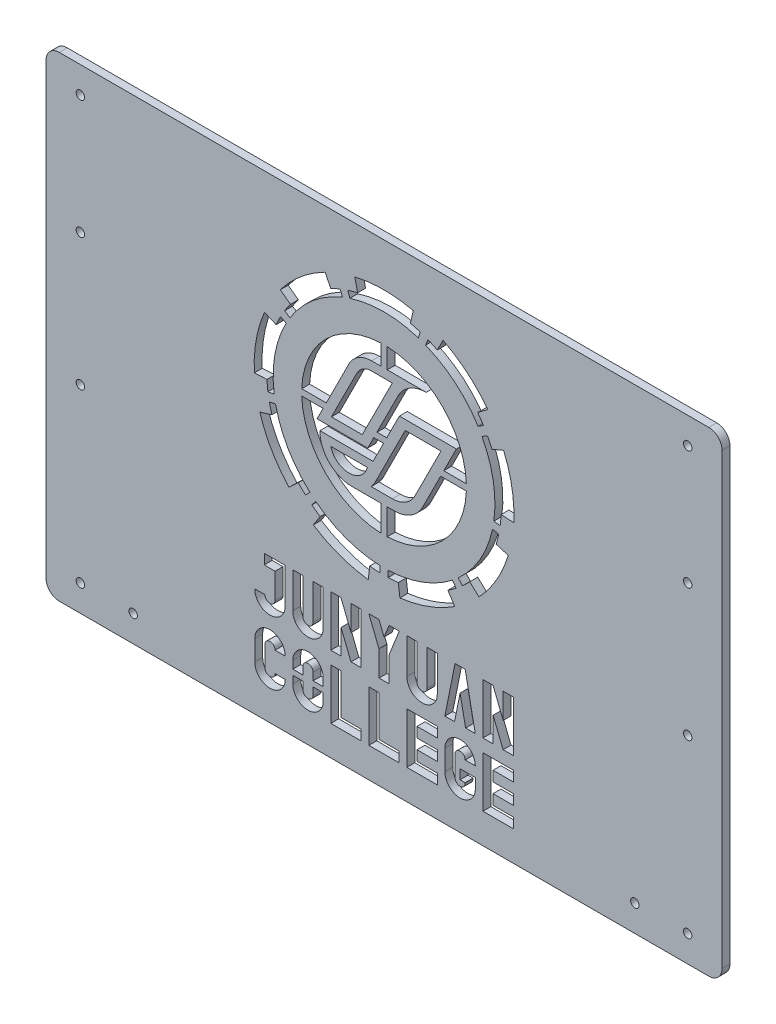
SolidWorks part; units mm, degrees
material "Thornel Mat VMA"
ref_plane "Front Plane" through (0, 0, 0) normal (0, 0, 1) x (1, 0, 0)
ref_plane "Top Plane" through (0, 0, 0) normal (0, 1, 0) x (1, 0, 0)
ref_plane "Right Plane" through (0, 0, 0) normal (1, 0, 0) x (0, 0, -1)
sketch "Model" plane through (0, 0, 0) normal (0, 0, 1) x (1, 0, 0)
  line L0 (140.7037, 160.9684) -> (141.7835, 165.6454)
  line L1 (120.728, 160.9684) -> (119.6483, 165.6454)
  line L2 (110.5587, 157.2671) -> (108.3795, 161.5439)
  line L3 (95.2564, 144.427) -> (91.423, 147.3157)
  line L4 (89.8454, 135.0549) -> (85.427, 136.9304)
  line L5 (86.3767, 115.3827) -> (81.5833, 115.1315)
  line L6 (88.2559, 104.7251) -> (83.6657, 103.3217)
  line L7 (98.2438, 87.4257) -> (94.7333, 84.1521)
  line L8 (106.5339, 80.4694) -> (103.9196, 76.4438)
  line L9 (125.3049, 73.6374) -> (124.7199, 68.8731)
  line L10 (136.1269, 73.6374) -> (136.7118, 68.8731)
  line L11 (154.8978, 80.4694) -> (157.5121, 76.4438)
  line L12 (163.188, 87.4257) -> (166.6985, 84.1521)
  line L13 (173.1758, 104.7251) -> (177.7661, 103.3217)
  line L14 (175.055, 115.3827) -> (179.8484, 115.1315)
  line L15 (171.5863, 135.0549) -> (176.0047, 136.9304)
  line L16 (166.1753, 144.427) -> (170.0087, 147.3157)
  line L17 (150.873, 157.2671) -> (153.0522, 161.5439)
  line L18 (136.5243, 128.4339) -> (158.1243, 128.4339)
  line L19 (138.745, 124.8339) -> (152.2882, 124.8339)
  line L20 (136.5243, 128.4339) -> (131.7401, 118.9064)
  line L21 (130.535, 116.5064) -> (126.5615, 108.5934)
  line L22 (138.745, 124.8339) -> (127.4637, 102.3677)
  line L23 (126.5615, 108.5934) -> (106.429, 108.5934)
  line L24 (124.4082, 105.5236) -> (110.5023, 105.5236)
  line L25 (158.1243, 128.4339) -> (153.3401, 118.9064)
  line L26 (152.135, 116.5064) -> (145.3412, 102.9771)
  line L27 (152.2882, 124.8339) -> (142.4563, 105.2541)
  line L28 (118.4268, 96.3621) -> (129.5159, 96.3621)
  line L29 (131.9159, 96.3621) -> (134.6174, 96.3621)
  line L30 (125.8338, 99.9621) -> (133.8771, 99.9621)
  line L31 (124.5428, 111.9383) -> (105.3428, 111.9383)
  line L32 (122.4702, 115.2983) -> (110.7898, 115.2983)
  line L33 (135.9593, 134.6735) -> (128.0418, 118.9064)
  line L34 (126.8367, 116.5064) -> (124.5428, 111.9383)
  line L35 (133.8339, 137.9285) -> (122.4702, 115.2983)
  line L36 (117.4236, 135.9965) -> (108.8418, 118.9064)
  line L37 (107.6367, 116.5064) -> (105.3428, 111.9383)
  line L38 (120.4263, 134.4887) -> (110.7898, 115.2983)
  line L39 (126.0027, 141.2885) -> (129.5159, 141.2885)
  line L40 (131.9159, 141.2885) -> (146.6831, 141.2885)
  line L41 (87.2861, 108.4751) -> (89.6337, 108.9741)
  line L42 (116.9955, 159.9333) -> (117.7371, 157.6508)
  line L43 (169.9187, 138.551) -> (167.7997, 137.4242)
  line L44 (126.0027, 137.9285) -> (133.8339, 137.9285)
  line L45 (160.4253, 84.7108) -> (158.8193, 86.4943)
  line L46 (114.0833, 158.8734) -> (114.9824, 156.6481)
  line L47 (86.748, 111.5271) -> (89.1246, 111.8611)
  line L48 (168.3692, 141.2348) -> (166.3339, 139.963)
  line L49 (158.0512, 82.7187) -> (156.5736, 84.61)
  line L50 (129.5159, 141.2885) -> (129.5159, 148.8833)
  line L51 (131.9159, 141.2885) -> (131.9159, 148.8833)
  line L52 (129.5159, 96.3621) -> (129.5159, 86.5295)
  line L53 (131.9159, 96.3621) -> (131.9159, 86.5295)
  line L54 (99.5389, 118.9064) -> (108.8418, 118.9064)
  line L55 (107.6367, 116.5064) -> (99.5389, 116.5064)
  line L56 (153.3401, 118.9064) -> (161.8928, 118.9064)
  line L57 (152.135, 116.5064) -> (161.8928, 116.5064)
  line L58 (128.0418, 118.9064) -> (131.7401, 118.9064)
  line L59 (126.8367, 116.5064) -> (130.535, 116.5064)
  line L60 (85.3559, 57.848) -> (93.2759, 57.848)
  line L61 (93.2759, 57.848) -> (93.2759, 44.408)
  line L62 (85.3559, 57.848) -> (85.3559, 54.008)
  line L63 (85.3559, 54.008) -> (89.4359, 54.008)
  line L64 (89.4359, 54.008) -> (89.4359, 44.408)
  line L65 (85.5959, 44.408) -> (81.7559, 44.408)
  line L66 (107.6759, 57.848) -> (107.6759, 44.408)
  line L67 (103.8359, 57.848) -> (103.8359, 44.408)
  line L68 (103.8359, 57.848) -> (107.6759, 57.848)
  line L69 (96.1559, 57.848) -> (96.1559, 44.408)
  line L70 (99.9959, 57.848) -> (99.9959, 44.408)
  line L71 (99.9959, 57.848) -> (96.1559, 57.848)
  line L72 (122.0759, 57.848) -> (122.0759, 38.648)
  line L73 (118.2359, 57.848) -> (118.2359, 48.248)
  line L74 (110.5559, 57.848) -> (110.5559, 38.648)
  line L75 (114.4323, 48.0636) -> (114.4673, 38.648)
  line L76 (114.3959, 57.848) -> (118.2359, 48.248)
  line L77 (114.4323, 48.0636) -> (118.1985, 38.648)
  line L78 (122.0759, 38.648) -> (118.1985, 38.648)
  line L79 (110.5559, 57.848) -> (114.3959, 57.848)
  line L80 (118.2359, 57.848) -> (122.0759, 57.848)
  line L81 (110.5559, 38.648) -> (114.4673, 38.648)
  line L82 (128.7959, 48.248) -> (128.8309, 38.648)
  line L83 (128.7959, 57.848) -> (130.7159, 53.048)
  line L84 (124.9559, 57.848) -> (128.7959, 57.848)
  line L85 (132.6359, 57.848) -> (136.4759, 57.848)
  line L86 (132.6359, 57.848) -> (130.7159, 53.048)
  line L87 (124.9559, 57.848) -> (128.7959, 48.248)
  line L88 (136.4759, 57.848) -> (132.6359, 48.248)
  line L89 (132.6359, 48.248) -> (132.6008, 38.648)
  line L90 (128.8309, 38.648) -> (132.6008, 38.648)
  line L91 (150.8759, 57.848) -> (150.8759, 44.408)
  line L92 (147.0359, 57.848) -> (147.0359, 44.408)
  line L93 (147.0359, 57.848) -> (150.8759, 57.848)
  line L94 (139.3559, 57.848) -> (139.3559, 44.408)
  line L95 (143.1959, 57.848) -> (143.1959, 44.408)
  line L96 (143.1959, 57.848) -> (139.3559, 57.848)
  line L97 (165.2759, 38.648) -> (161.6046, 38.648)
  line L98 (153.7559, 38.648) -> (157.4272, 38.648)
  line L99 (153.7559, 38.648) -> (157.5959, 57.848)
  line L100 (157.4272, 38.648) -> (159.5159, 49.0915)
  line L101 (157.5959, 57.848) -> (161.4359, 57.848)
  line L102 (161.4359, 57.848) -> (165.2759, 38.648)
  line L103 (161.6046, 38.648) -> (159.5159, 49.0915)
  line L104 (179.6759, 57.848) -> (179.6759, 38.648)
  line L105 (175.8359, 57.848) -> (175.8359, 48.248)
  line L106 (168.1559, 57.848) -> (168.1559, 38.648)
  line L107 (172.0323, 48.0636) -> (172.0673, 38.648)
  line L108 (171.9959, 57.848) -> (175.8359, 48.248)
  line L109 (172.0323, 48.0636) -> (175.7985, 38.648)
  line L110 (179.6759, 38.648) -> (175.7985, 38.648)
  line L111 (168.1559, 57.848) -> (171.9959, 57.848)
  line L112 (175.8359, 57.848) -> (179.6759, 57.848)
  line L113 (168.1559, 38.648) -> (172.0673, 38.648)
  line L114 (81.7559, 28.088) -> (81.7559, 20.408)
  line L115 (85.5959, 28.088) -> (85.5959, 20.408)
  line L116 (89.4359, 28.088) -> (93.2759, 28.088)
  line L117 (89.4359, 20.408) -> (93.2759, 20.408)
  line L118 (96.1559, 28.088) -> (96.1559, 25.248)
  line L119 (99.9959, 28.088) -> (99.9959, 25.248)
  line L120 (107.6759, 28.088) -> (107.6759, 25.248)
  line L121 (103.8359, 28.088) -> (103.8359, 25.248)
  line L122 (110.5559, 33.848) -> (110.5559, 14.648)
  line L123 (114.3959, 33.848) -> (114.3959, 18.488)
  line L124 (114.3959, 33.848) -> (110.5559, 33.848)
  line L125 (110.5559, 14.648) -> (122.0759, 14.648)
  line L126 (122.0759, 14.648) -> (122.0759, 18.488)
  line L127 (122.0759, 18.488) -> (114.3959, 18.488)
  line L128 (124.9559, 33.848) -> (124.9559, 14.648)
  line L129 (128.7959, 33.848) -> (128.7959, 18.488)
  line L130 (128.7959, 33.848) -> (124.9559, 33.848)
  line L131 (124.9559, 14.648) -> (136.4759, 14.648)
  line L132 (136.4759, 14.648) -> (136.4759, 18.488)
  line L133 (136.4759, 18.488) -> (128.7959, 18.488)
  line L134 (139.3559, 33.848) -> (139.3559, 14.648)
  line L135 (143.1959, 30.008) -> (143.1959, 26.168)
  line L136 (143.1959, 22.328) -> (143.1959, 18.488)
  line L137 (143.1959, 33.848) -> (139.3559, 33.848)
  line L138 (139.3559, 14.648) -> (150.8759, 14.648)
  line L139 (150.8759, 14.648) -> (150.8759, 18.488)
  line L140 (150.8759, 18.488) -> (143.1959, 18.488)
  line L141 (139.3559, 33.848) -> (150.8759, 33.848)
  line L142 (150.8759, 33.848) -> (150.8759, 30.008)
  line L143 (150.8759, 30.008) -> (143.1959, 30.008)
  line L144 (143.1959, 26.168) -> (150.8759, 26.168)
  line L145 (150.8759, 26.168) -> (150.8759, 22.328)
  line L146 (150.8759, 22.328) -> (143.1959, 22.328)
  line L147 (168.1559, 33.848) -> (168.1559, 14.648)
  line L148 (171.9959, 30.008) -> (171.9959, 26.168)
  line L149 (171.9959, 22.328) -> (171.9959, 18.488)
  line L150 (171.9959, 33.848) -> (168.1559, 33.848)
  line L151 (168.1559, 14.648) -> (179.6759, 14.648)
  line L152 (179.6759, 14.648) -> (179.6759, 18.488)
  line L153 (179.6759, 18.488) -> (171.9959, 18.488)
  line L154 (168.1559, 33.848) -> (179.6759, 33.848)
  line L155 (179.6759, 33.848) -> (179.6759, 30.008)
  line L156 (179.6759, 30.008) -> (171.9959, 30.008)
  line L157 (171.9959, 26.168) -> (179.6759, 26.168)
  line L158 (179.6759, 26.168) -> (179.6759, 22.328)
  line L159 (179.6759, 22.328) -> (171.9959, 22.328)
  line L160 (153.7559, 28.088) -> (153.7559, 20.408)
  line L161 (157.5959, 28.088) -> (157.5959, 20.408)
  line L162 (161.4359, 28.088) -> (165.2759, 28.088)
  line L163 (165.2759, 24.248) -> (165.2759, 20.408)
  line L164 (161.4359, 20.648) -> (159.5159, 20.648)
  line L165 (159.5159, 20.648) -> (159.5159, 24.248)
  line L166 (159.5159, 24.248) -> (165.2759, 24.248)
  line L167 (161.4359, 20.648) -> (161.4359, 20.408)
  line L168 (7.7159, 183.309) -> (253.7159, 183.309)
  line L169 (2.7159, 178.309) -> (2.7159, 8.309)
  line L170 (7.7159, 3.309) -> (253.7159, 3.309)
  line L171 (258.7159, 8.309) -> (258.7159, 178.309)
  line L172 (147.3484, 158.8734) -> (146.4493, 156.6481)
  line L173 (144.4362, 159.9333) -> (143.6946, 157.6508)
  line L174 (174.1456, 108.4751) -> (171.7981, 108.9741)
  line L175 (174.6838, 111.5271) -> (172.3071, 111.8611)
  line L176 (93.0625, 141.2348) -> (95.0978, 139.963)
  line L177 (91.513, 138.551) -> (93.6321, 137.4242)
  line L178 (103.3805, 82.7187) -> (104.8581, 84.61)
  line L179 (101.0065, 84.7108) -> (102.6124, 86.4943)
  line L180 (132.2654, 73.3335) -> (132.1816, 75.732)
  line L181 (129.1663, 73.3335) -> (129.2501, 75.732)
  line L182 (99.9959, 25.248) -> (96.1559, 25.248)
  line L183 (99.9959, 23.248) -> (96.1559, 23.248)
  line L184 (103.8359, 25.248) -> (107.6759, 25.248)
  line L185 (103.8359, 23.248) -> (107.6759, 23.248)
  line L186 (107.6759, 23.248) -> (107.6759, 20.408)
  line L187 (103.8359, 23.248) -> (103.8359, 20.408)
  line L188 (99.9959, 23.248) -> (99.9959, 20.408)
  line L189 (96.1559, 23.248) -> (96.1559, 20.408)
  circle A0 centre (15.7159, 173.309) radius 1.6
  circle A1 centre (15.7159, 128.309) radius 1.6
  circle A2 centre (15.7159, 78.309) radius 1.6
  circle A3 centre (245.7159, 173.309) radius 1.6
  circle A4 centre (245.7159, 128.309) radius 1.6
  circle A5 centre (245.7159, 78.309) radius 1.6
  arc A6 (129.5159, 148.8833) -> (99.5389, 118.9064) centre (130.7159, 117.7064) ccw
  arc A7 (99.5389, 116.5064) -> (129.5159, 86.5295) centre (130.7159, 117.7064) ccw
  arc A8 (131.9159, 86.5295) -> (161.8928, 116.5064) centre (130.7159, 117.7064) ccw
  arc A9 (161.8928, 118.9064) -> (131.9159, 148.8833) centre (130.7159, 117.7064) ccw
  arc A10 (114.9824, 156.6481) -> (95.0978, 139.963) centre (130.7159, 117.7064) ccw
  arc A11 (93.6321, 137.4242) -> (89.1246, 111.8611) centre (130.7159, 117.7064) ccw
  arc A12 (89.6337, 108.9741) -> (102.6124, 86.4943) centre (130.7159, 117.7064) ccw
  arc A13 (104.8581, 84.61) -> (129.2501, 75.732) centre (130.7159, 117.7064) ccw
  arc A14 (132.1816, 75.732) -> (156.5736, 84.61) centre (130.7159, 117.7064) ccw
  arc A15 (158.8193, 86.4943) -> (171.7981, 108.9741) centre (130.7159, 117.7064) ccw
  arc A16 (172.3071, 111.8611) -> (167.7997, 137.4242) centre (130.7159, 117.7064) ccw
  arc A17 (166.3339, 139.963) -> (146.4493, 156.6481) centre (130.7159, 117.7064) ccw
  arc A18 (143.6946, 157.6508) -> (117.7371, 157.6508) centre (130.7159, 117.7064) ccw
  arc A19 (141.7835, 165.6454) -> (119.6483, 165.6454) centre (130.7159, 117.7064) ccw
  arc A20 (108.3795, 161.5439) -> (91.423, 147.3157) centre (130.7159, 117.7064) ccw
  arc A21 (85.427, 136.9304) -> (81.5833, 115.1315) centre (130.7159, 117.7064) ccw
  arc A22 (83.6657, 103.3217) -> (94.7333, 84.1521) centre (130.7159, 117.7064) ccw
  arc A23 (103.9196, 76.4438) -> (124.7199, 68.8731) centre (130.7159, 117.7064) ccw
  arc A24 (136.7118, 68.8731) -> (157.5121, 76.4438) centre (130.7159, 117.7064) ccw
  arc A25 (166.6985, 84.1521) -> (177.7661, 103.3217) centre (130.7159, 117.7064) ccw
  arc A26 (179.8484, 115.1315) -> (176.0047, 136.9304) centre (130.7159, 117.7064) ccw
  arc A27 (170.0087, 147.3157) -> (153.0522, 161.5439) centre (130.7159, 117.7064) ccw
  arc A28 (120.728, 160.9684) -> (116.9955, 159.9333) centre (130.7159, 117.7064) ccw
  arc A29 (114.0833, 158.8734) -> (110.5587, 157.2671) centre (130.7159, 117.7064) ccw
  arc A30 (95.2564, 144.427) -> (93.0625, 141.2348) centre (130.7159, 117.7064) ccw
  arc A31 (91.513, 138.551) -> (89.8454, 135.0549) centre (130.7159, 117.7064) ccw
  arc A32 (86.3767, 115.3827) -> (86.748, 111.5271) centre (130.7159, 117.7064) ccw
  arc A33 (87.2861, 108.4751) -> (88.2559, 104.7251) centre (130.7159, 117.7064) ccw
  arc A34 (98.2438, 87.4257) -> (101.0065, 84.7108) centre (130.7159, 117.7064) ccw
  arc A35 (103.3805, 82.7187) -> (106.5339, 80.4694) centre (130.7159, 117.7064) ccw
  arc A36 (125.3049, 73.6374) -> (129.1663, 73.3335) centre (130.7159, 117.7064) ccw
  arc A37 (132.2654, 73.3335) -> (136.1269, 73.6374) centre (130.7159, 117.7064) ccw
  arc A38 (154.8978, 80.4694) -> (158.0512, 82.7187) centre (130.7159, 117.7064) ccw
  arc A39 (160.4253, 84.7108) -> (163.188, 87.4257) centre (130.7159, 117.7064) ccw
  arc A40 (173.1758, 104.7251) -> (174.1456, 108.4751) centre (130.7159, 117.7064) ccw
  arc A41 (174.6838, 111.5271) -> (175.055, 115.3827) centre (130.7159, 117.7064) ccw
  arc A42 (171.5863, 135.0549) -> (169.9187, 138.551) centre (130.7159, 117.7064) ccw
  arc A43 (168.3692, 141.2348) -> (166.1753, 144.427) centre (130.7159, 117.7064) ccw
  arc A44 (150.873, 157.2671) -> (147.3484, 158.8734) centre (130.7159, 117.7064) ccw
  arc A45 (144.4362, 159.9333) -> (140.7037, 160.9684) centre (130.7159, 117.7064) ccw
  arc A46 (133.8771, 99.9621) -> (142.4563, 105.2541) centre (133.8771, 109.5621) ccw
  arc A47 (134.6174, 96.3621) -> (145.3412, 102.9771) centre (134.6174, 108.3621) ccw
  arc A48 (106.429, 108.5934) -> (118.4268, 96.3621) centre (118.4268, 108.3621) ccw
  arc A49 (110.5023, 105.5236) -> (124.4082, 105.5236) centre (117.4552, 107.3934) ccw
  arc A50 (125.8338, 99.9621) -> (127.4637, 102.3677) centre (117.4552, 107.3934) ccw
  arc A51 (146.6831, 141.2885) -> (135.9593, 134.6735) centre (146.6831, 129.2885) ccw
  arc A52 (126.0027, 141.2885) -> (117.4236, 135.9965) centre (126.0027, 131.6885) ccw
  arc A53 (126.0027, 137.9285) -> (120.4263, 134.4887) centre (126.0027, 131.6885) ccw
  arc A54 (81.7559, 44.408) -> (93.2759, 44.408) centre (87.5159, 44.408) ccw
  arc A55 (85.5959, 44.408) -> (89.4359, 44.408) centre (87.5159, 44.408) ccw
  arc A56 (96.1559, 44.408) -> (107.6759, 44.408) centre (101.9159, 44.408) ccw
  arc A57 (99.9959, 44.408) -> (103.8359, 44.408) centre (101.9159, 44.408) ccw
  arc A58 (139.3559, 44.408) -> (150.8759, 44.408) centre (145.1159, 44.408) ccw
  arc A59 (143.1959, 44.408) -> (147.0359, 44.408) centre (145.1159, 44.408) ccw
  arc A60 (81.7559, 20.408) -> (93.2759, 20.408) centre (87.5159, 20.408) ccw
  arc A61 (85.5959, 20.408) -> (89.4359, 20.408) centre (87.5159, 20.408) ccw
  arc A62 (93.2759, 28.088) -> (81.7559, 28.088) centre (87.5159, 28.088) ccw
  arc A63 (89.4359, 28.088) -> (85.5959, 28.088) centre (87.5159, 28.088) ccw
  arc A64 (96.1559, 20.408) -> (107.6759, 20.408) centre (101.9159, 20.408) ccw
  arc A65 (99.9959, 20.408) -> (103.8359, 20.408) centre (101.9159, 20.408) ccw
  arc A66 (107.6759, 28.088) -> (96.1559, 28.088) centre (101.9159, 28.088) ccw
  arc A67 (103.8359, 28.088) -> (99.9959, 28.088) centre (101.9159, 28.088) ccw
  arc A68 (153.7559, 20.408) -> (165.2759, 20.408) centre (159.5159, 20.408) ccw
  arc A69 (157.5959, 20.408) -> (161.4359, 20.408) centre (159.5159, 20.408) ccw
  arc A70 (165.2759, 28.088) -> (153.7559, 28.088) centre (159.5159, 28.088) ccw
  arc A71 (161.4359, 28.088) -> (157.5959, 28.088) centre (159.5159, 28.088) ccw
  arc A72 (258.7159, 178.309) -> (253.7159, 183.309) centre (253.7159, 178.309) ccw
  arc A73 (7.7159, 183.309) -> (2.7159, 178.309) centre (7.7159, 178.309) ccw
  arc A74 (2.7159, 8.309) -> (7.7159, 3.309) centre (7.7159, 8.309) ccw
  arc A75 (253.7159, 3.309) -> (258.7159, 8.309) centre (253.7159, 8.309) ccw
  circle A76 centre (15.7159, 13.309) radius 1.6
  circle A77 centre (245.7159, 13.309) radius 1.6
  circle A78 centre (35.7159, 13.309) radius 1.6
  circle A79 centre (225.7159, 13.309) radius 1.6
extrude "Boss-Extrude1" add sketch "Model" along normal blind 3 contours L170 A75 L171 A72 L168 A73 L169 A74 A79 A78 A77 A76 L162 A71 L161 A69 L167 L164 L165 L166 L163 A68 L160 A70 L121 A67 L119 L182 L118 A66 L120 L184 L188 A65 L187 L185 L186 A64 L189 L183 L116 A63 L115
